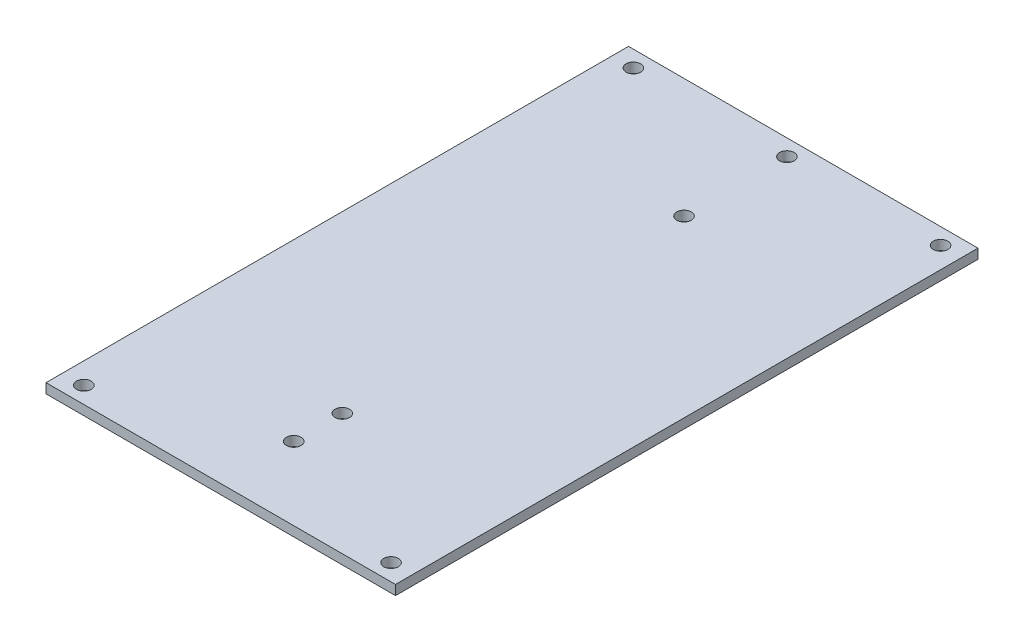
SolidWorks part; units mm, degrees
ref_plane "Front Plane" through (0, 0, 0) normal (0, 0, 1) x (1, 0, 0)
ref_plane "Top Plane" through (0, 0, 0) normal (0, 1, 0) x (1, 0, 0)
ref_plane "Right Plane" through (0, 0, 0) normal (1, 0, 0) x (0, 0, -1)
sketch "Sketch1" plane through (0, 0, 0) normal (0, 1, 0) x (1, 0, 0)
  line L0 (0, -146.05) -> (0, 146.05) construction
  line L5 (-100.457, 213.36) -> (100.457, 213.36)
  line L6 (0, 213.36) -> (0, -109.22) construction
  line L7 (-100.457, -146.05) -> (100.457, -146.05)
  line L8 (0, -146.05) -> (0, 213.36) construction
  line L9 (-114.3, 224.028) -> (114.3, 224.028)
  line L10 (114.3, 224.028) -> (114.3, -156.972)
  line L11 (114.3, -156.972) -> (-114.3, -156.972)
  line L12 (-114.3, -156.972) -> (-114.3, 224.028)
  circle A0 centre (0, 146.05) radius 4.7625
  circle A1 centre (-100.457, -146.05) radius 4.7625
  circle A2 centre (100.457, -146.05) radius 4.7625
  circle A3 centre (0, 213.36) radius 4.7625
  circle A4 centre (0, -109.22) radius 4.7625
  circle A5 centre (-100.457, 213.36) radius 4.7625
  circle A6 centre (100.457, 213.36) radius 4.7625
  circle A7 centre (0, -77.47) radius 4.7625
  point P0 (0, 0)
  point P8 (0, 0)
  point P13 (0, -146.05)
  point P19 (0, 213.36)
  point P24 (0, 0)
  point P27 (0, -156.972)
  point P28 (0, 0)
  point P29 (0, 0)
  dimension "D4" = 9.525
  dimension "D1" = 359.41
  dimension "D2" = 322.58
  dimension "D3" = 292.1
  dimension "D5" = 200.914
  dimension "D6" = 290.83
  dimension "D7" = 228.6
  dimension "D8" = 381
  dimension "D9" = 10.922
extrude "Boss-Extrude1" add sketch "Sketch1" along normal blind 6.35
